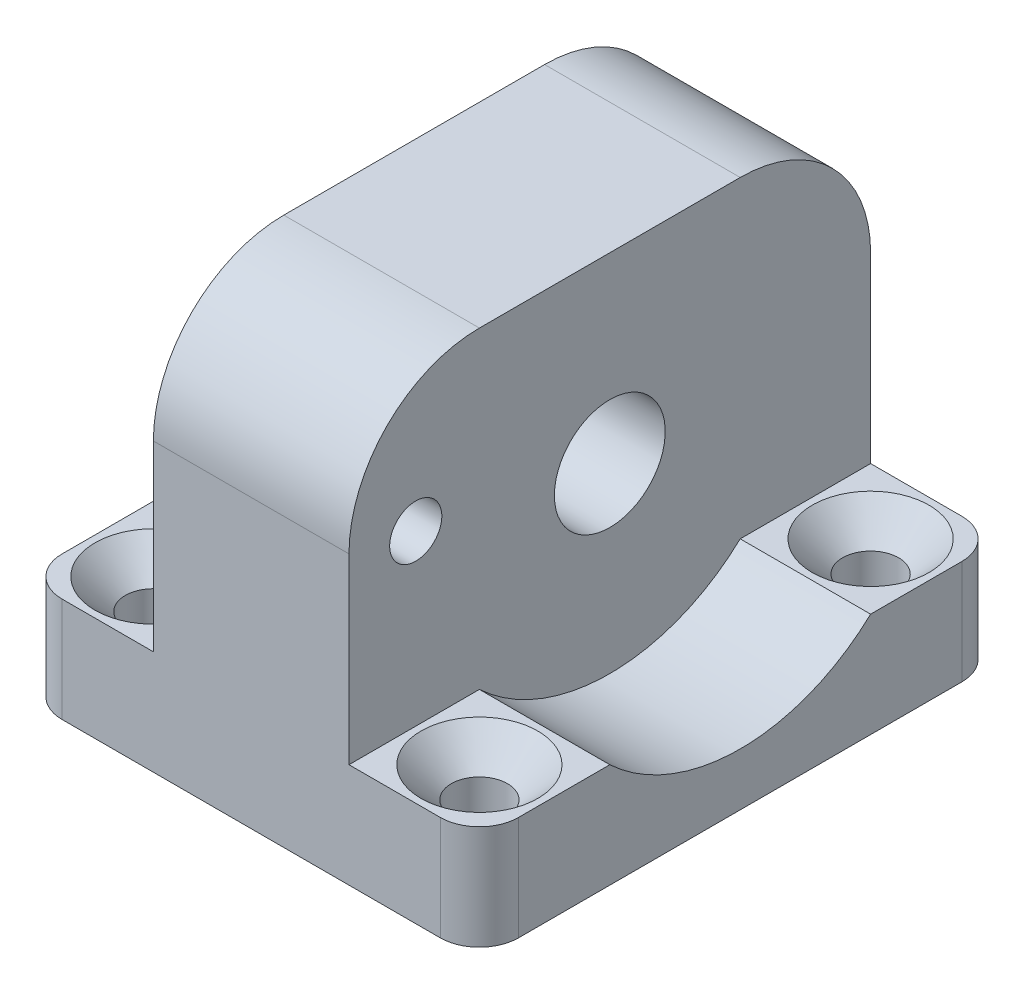
SolidWorks part; units mm, degrees
ref_plane "前视基准面" through (0, 0, 0) normal (0, 0, 1) x (1, 0, 0)
ref_plane "上视基准面" through (0, 0, 0) normal (0, 1, 0) x (1, 0, 0)
ref_plane "右视基准面" through (0, 0, 0) normal (1, 0, 0) x (0, 0, -1)
sketch "草图2" plane through (0, 0, 0) normal (0, 1, 0) x (1, 0, 0)
  line L1 (-17.5, 20) -> (17.5, 20)
  line L2 (-17.5, 20) -> (-17.5, -20)
  line L3 (-17.5, -20) -> (17.5, -20)
  line L4 (17.5, 20) -> (17.5, -20)
  line L5 (-17.5, 20) -> (17.5, -20) construction
  line L6 (-17.5, -20) -> (17.5, 20) construction
  point P0 (0, 0)
  dimension "D1" = 40
  dimension "D2" = 35
extrude "凸台-拉伸1" add sketch "草图2" along normal blind 8
sketch "草图3" plane through (0, 8, 0) normal (0, 1, 0) x (1, 0, 0)
  line L1 (-12.5, 15) -> (12.5, 15)
  line L2 (-12.5, 15) -> (-12.5, -15)
  line L3 (-12.5, -15) -> (12.5, -15)
  line L4 (12.5, 15) -> (12.5, -15)
  line L5 (-12.5, 15) -> (12.5, -15) construction
  line L6 (-12.5, -15) -> (12.5, 15) construction
  circle A0 centre (12.5, 15) radius 2
  circle A1 centre (-12.5, 15) radius 2
  circle A2 centre (-12.5, -15) radius 2
  circle A3 centre (12.5, -15) radius 2
  point P0 (0, 0)
  dimension "D3" = 4
  dimension "D4" = 4
  dimension "D5" = 4
  dimension "D6" = 4
  dimension "D1" = 30
  dimension "D2" = 25
extrude "切除-拉伸2" cut sketch "草图3" against normal blind 10 contours A1 | A2 | A3 | A0
sketch "草图4" plane through (0, 8, 0) normal (0, 1, 0) x (1, 0, 0)
  line L0 (-17.5, -20) -> (17.5, -20) construction
  line L1 (-7.5, 20) -> (7.5, 20)
  line L2 (-7.5, 20) -> (-7.5, -20)
  line L3 (-7.5, -20) -> (7.5, -20)
  line L4 (7.5, 20) -> (7.5, -20)
  line L5 (-7.5, 20) -> (7.5, -20) construction
  line L6 (-7.5, -20) -> (7.5, 20) construction
  point P0 (0, 0)
  dimension "D1" = 15
extrude "凸台-拉伸2" add sketch "草图4" along normal blind 24
sketch "草图5" plane through (7.5, 0, 0) normal (1, 0, 0) x (0, 0, -1)
  line L0 (-20, 8) -> (20, 8) construction
  circle A0 centre (0, 18) radius 6.2
  dimension "D1" = 10
extrude "切除-拉伸3" cut sketch "草图5" against normal through all
sketch "草图6" plane through (7.5, 0, 0) normal (1, 0, 0) x (0, 0, -1)
  circle A0 centre (0, 18) radius 10
extrude "切除-拉伸4" cut sketch "草图6" against normal blind 3
fillet "圆角2" radius 3 4 edges at (17.5, 4, -20) (-17.5, 4, -20) (-17.5, 4, 20) (17.5, 4, 20)
fillet "圆角3" radius 10 2 edges at (0, 32, 20) (0, 32, -20)
hole_wizard "M4 六角凹锥坑螺钉的锥形沉头孔1" positions "草图7" profile "草图8" countersink size "M4" standard "ISO" end condition up to next
sketch "草图7" plane through (0, 8, 0) normal (0, 1, 0) x (1, 0, 0)
  point P0 (12.5, -15)
  point P3 (12.5, 15)
  point P6 (-12.5, 15)
  point P9 (-12.5, -15)
sketch "草图8" plane through (12.5, 8, 15) normal (1, 0, 0) x (0, 0, 1)
  line L0 (0, 0) -> (0, 8)
  line L1 (0, 8) -> (2.15, 8)
  line L2 (2.15, 8) -> (2.15, 2.33)
  line L3 (2.15, 2.33) -> (4.48, 0)
  line L5 (4.48, 0) -> (0, 0)
  line L6 (-2.15, 2.33) -> (-4.48, 0) construction
  line L11 (0, -6.35) -> (0, 107.95) construction
  dimension "通孔孔直径" = 4.3
  dimension "通孔孔深度" = 8
  dimension "近端锥形沉头孔直径" = 8.96
  dimension "近端锥形沉头孔角度" = 90
sketch "草图9" plane through (7.5, 0, 0) normal (1, 0, 0) x (0, 0, -1)
  circle A0 centre (0, 18) radius 10
extrude "凸台-拉伸3" add sketch "草图9" against normal blind 3
sketch "草图10" plane through (4.5, 0, 0) normal (-1, 0, 0) x (0, 0, 1)
  circle A0 centre (0, 18) radius 4.25
  dimension "D1" = 8.5
extrude "切除-拉伸5" cut sketch "草图10" against normal blind 3
ref_plane "基准面1" through (-12.5, 0, 0) normal (-1, 0, 0) x (0, 0, 1)
sketch "草图12" plane through (-12.5, 0, 0) normal (-1, 0, 0) x (0, 0, 1)
  line L0 (-10, 8) -> (10, 8)
  line L1 (-20, 8) -> (20, 8) construction
  line L2 (10, 8) -> (10, 5) construction
  line L3 (10, 5) -> (-10, 5) construction
  line L4 (0, 5) -> (0, 8) construction
  line L5 (-10, 8) -> (-10, 5) construction
  arc A0 (-10, 8) -> (10, 8) centre (0, 18.6661) ccw
  dimension "D1" = 10
  dimension "D2" = 3
extrude "切除-拉伸6" cut sketch "草图12" against normal mid plane 10
ref_plane "基准面2" through (0, 0, 0) normal (-1, 0, 0) x (0, 0, 1)
mirror "镜向1" about plane through (0, 0, 0) normal (-1, 0, 0) of "切除-拉伸6"
sketch "草图14" plane through (4.5, 0, 0) normal (-1, 0, 0) x (0, 0, 1)
  circle A0 centre (0, 18) radius 4.25
  circle A1 centre (0, 18) radius 6.2
extrude "凸台-拉伸4" add sketch "草图14" along normal up to surface (12 mm away) up to face at (-7.5, 18, -6.2)
sketch "草图15" plane through (-7.5, 0, 0) normal (-1, 0, 0) x (0, 0, 1)
  line L0 (0, 18) -> (23.8517, 18) construction
  line L1 (5.7453, 13.1791) -> (19.8978, 30.0454) construction
  circle A0 centre (0, 18) radius 7.5 construction
  circle A1 centre (14.883, 20.9575) radius 2
  dimension "D1" = 15
  dimension "D2" = 50
extrude "切除-拉伸8" cut sketch "草图15" against normal blind 22
